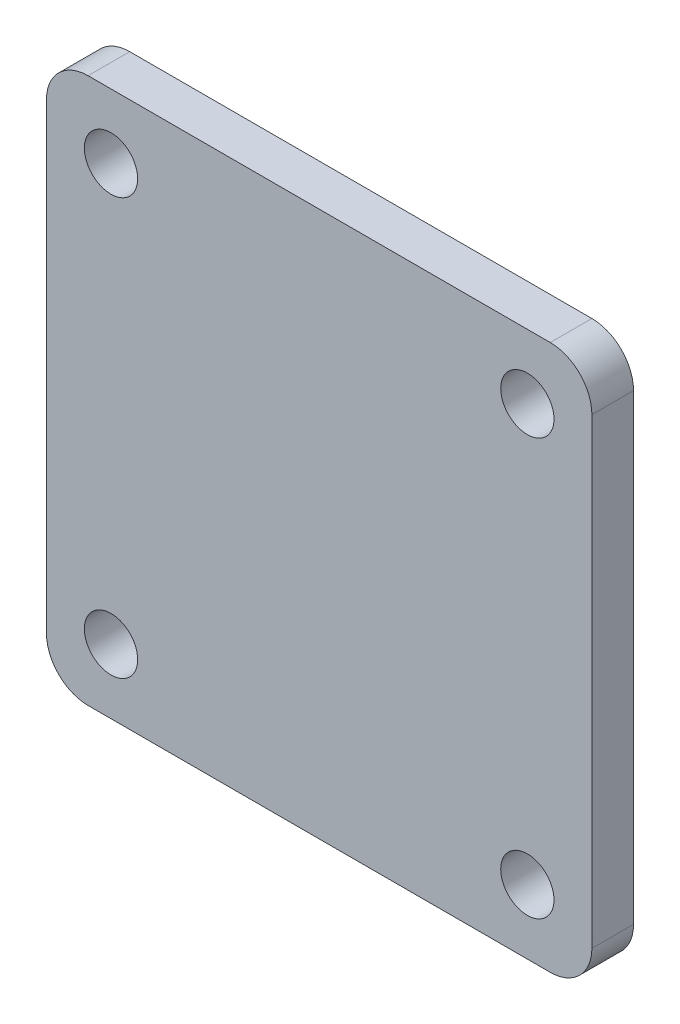
SolidWorks part; units mm, degrees
ref_plane "정면" through (0, 0, 0) normal (0, 0, 1) x (1, 0, 0)
ref_plane "윗면" through (0, 0, 0) normal (0, 1, 0) x (1, 0, 0)
ref_plane "우측면" through (0, 0, 0) normal (1, 0, 0) x (0, 0, -1)
sketch "스케치1" plane through (0, 0, 0) normal (0, 0, 1) x (1, 0, 0)
  line L1 (-32.75, -32.75) -> (32.75, -32.75)
  line L2 (-32.75, -32.75) -> (-32.75, 32.75)
  line L3 (-32.75, 32.75) -> (32.75, 32.75)
  line L4 (32.75, -32.75) -> (32.75, 32.75)
  line L5 (-32.75, -32.75) -> (32.75, 32.75) construction
  line L6 (-32.75, 32.75) -> (32.75, -32.75) construction
  point P0 (0, 0)
extrude "보스-돌출1" add sketch "스케치1" along normal blind 5 contours L3 L4 L1 L2
fillet "필렛1" radius 5 4 edges at (-32.75, -32.75, 2.5) (32.75, -32.75, 2.5) (32.75, 32.75, 2.5) (-32.75, 32.75, 2.5)
sketch "스케치3" plane through (0, 0, 5) normal (0, 0, 1) x (1, 0, 0)
  line L0 (-25, 0) -> (7.75, 0) construction
  line L1 (0, 0) -> (32.75, 0) construction
  line L2 (32.75, -27.75) -> (32.75, 27.75) construction
  line L3 (-50, 0) -> (-17.25, 0) construction
  circle A0 centre (25, -25) radius 3.2
  circle A1 centre (25, 25) radius 3.2
  circle A2 centre (25, 0) radius 3.2
  circle A3 centre (0, -25) radius 3.2
  circle A4 centre (0, 25) radius 3.2
  circle A5 centre (0, 0) radius 3.2
  circle A6 centre (-25, -25) radius 3.2
  circle A7 centre (-25, 25) radius 3.2
  circle A8 centre (-25, 0) radius 3.2
  dimension "D1" = 25
  dimension "D5" = 3
  dimension "D2" = 25
  dimension "D3" = 7.75
  dimension "D4" = 7.75
sketch "스케치7" plane through (0, 0, 0) normal (0, 0, -1) x (-1, 0, 0)
  line L0 (32.75, 0) -> (-32.75, 0) construction
  line L1 (32.75, -27.75) -> (32.75, 27.75) construction
  line L2 (-32.75, -27.75) -> (-32.75, 27.75) construction
  circle A0 centre (-25, -25) radius 3.2
  circle A1 centre (-25, 25) radius 3.2
  dimension "D1" = 25
  dimension "D2" = 25
  dimension "D3" = 7.75
  dimension "D4" = 7.75
extrude "컷-돌출2" cut sketch "스케치7" against normal blind 5
extrude "컷-돌출3" cut sketch "스케치3" against normal blind 15
sketch "스케치12" plane through (0, 0, 5) normal (0, 0, 1) x (1, 0, 0)
  circle A0 centre (25, 0) radius 3.2
  circle A1 centre (0, 0) radius 3.2
  circle A2 centre (0, -25) radius 3.2
  circle A3 centre (0, 25) radius 3.2
  circle A4 centre (-25, 0) radius 3.2
extrude "보스-돌출3" add sketch "스케치12" against normal blind 5
